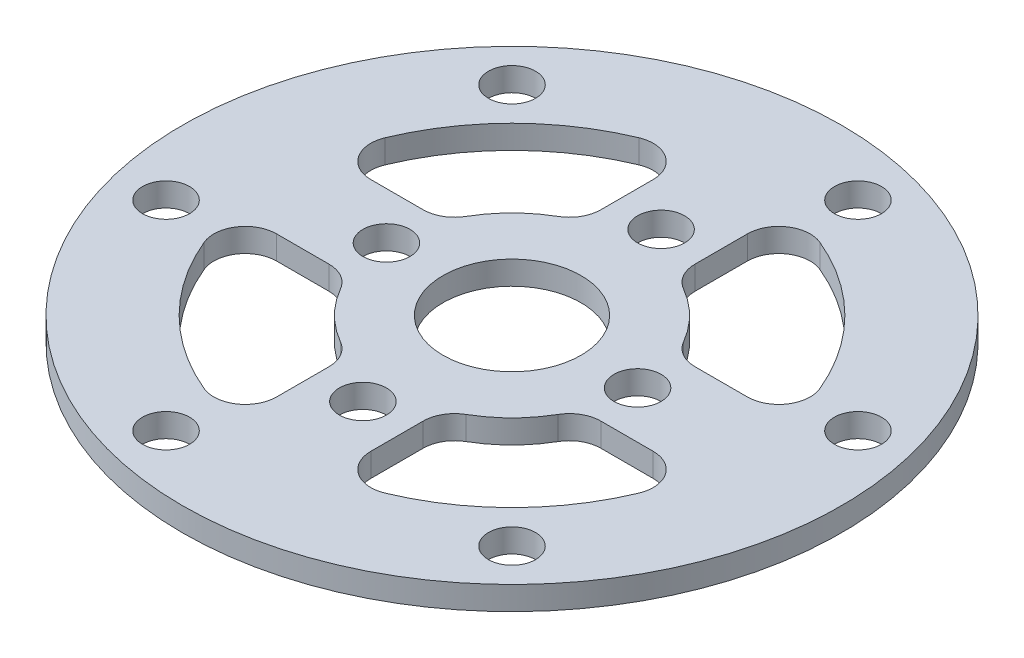
SolidWorks part; units mm, degrees
material "Thornel Mat VMA"
ref_plane "Front Plane" through (0, 0, 0) normal (0, 0, 1) x (1, 0, 0)
ref_plane "Top Plane" through (0, 0, 0) normal (0, 1, 0) x (1, 0, 0)
ref_plane "Right Plane" through (0, 0, 0) normal (1, 0, 0) x (0, 0, -1)
sketch "Sketch1" plane through (0, 0, 0) normal (0, 1, 0) x (1, 0, 0)
  line L0 (0, 0) -> (-21, 0) construction
  line L1 (0, 0) -> (0, 21) construction
  line L2 (0, 0) -> (21, 0) construction
  line L3 (0, 0) -> (0, -21) construction
  line L4 (-8.6603, 3) -> (-12, 3)
  line L5 (-8.6603, -3) -> (-12, -3)
  line L6 (-3, -8.6603) -> (-3, -12)
  line L7 (3, 8.6603) -> (3, 12)
  line L8 (8.6603, -3) -> (12, -3)
  line L9 (3, -8.6603) -> (3, -12)
  line L10 (-3, 8.6603) -> (-3, 12)
  line L11 (8.6603, 3) -> (12, 3)
  line L12 (-20.7846, -3) -> (-21, -3)
  line L13 (-3, -20.7846) -> (-3, -21)
  line L14 (0, -3) -> (-21, -3) construction
  line L15 (0, 3) -> (-21, 3) construction
  line L16 (-3, 0) -> (-3, -21) construction
  line L17 (-3, 0) -> (-3, 21) construction
  line L18 (0, 3) -> (21, 3) construction
  line L19 (3, 0) -> (3, 21) construction
  line L20 (3, 0) -> (3, -21) construction
  line L21 (0, -3) -> (21, -3) construction
  line L22 (-4.6587, -17.3867) -> (4.6587, 17.3867) construction
  line L23 (-17.3867, -4.6587) -> (17.3867, 4.6587) construction
  line L30 (12.7279, -12.7279) -> (-14.8492, 14.8492) construction
  circle A0 centre (0, 0) radius 4.4
  circle A1 centre (0, 0) radius 8 construction
  circle A2 centre (0, 0) radius 21
  arc A3 (-6.9282, -4) -> (-4, -6.9282) centre (0, 0) ccw
  arc A4 (-13.8462, -5.7692) -> (-5.7692, -13.8462) centre (0, 0) ccw
  arc A5 (5.7692, -13.8462) -> (13.8462, -5.7692) centre (0, 0) ccw
  arc A6 (4, -6.9282) -> (6.9282, -4) centre (0, 0) ccw
  arc A7 (6.9282, 4) -> (4, 6.9282) centre (0, 0) ccw
  arc A8 (13.8462, 5.7692) -> (5.7692, 13.8462) centre (0, 0) ccw
  arc A9 (-5.7692, -13.8462) -> (-3, -12) centre (-5, -12) ccw
  arc A10 (-3, -8.6603) -> (-4, -6.9282) centre (-5, -8.6603) ccw
  arc A11 (-6.9282, -4) -> (-8.6603, -3) centre (-8.6603, -5) ccw
  arc A12 (-12, -3) -> (-13.8462, -5.7692) centre (-12, -5) ccw
  arc A13 (-4, 6.9282) -> (-6.9282, 4) centre (0, 0) ccw
  arc A14 (-5.7692, 13.8462) -> (-13.8462, 5.7692) centre (0, 0) ccw
  arc A15 (-6.9282, 4) -> (-8.6603, 3) centre (-8.6603, 5) cw
  arc A16 (-13.8462, 5.7692) -> (-12, 3) centre (-12, 5) ccw
  arc A17 (-3, 8.6603) -> (-4, 6.9282) centre (-5, 8.6603) cw
  arc A18 (-3, 12) -> (-5.7692, 13.8462) centre (-5, 12) ccw
  arc A19 (8.6603, 3) -> (6.9282, 4) centre (8.6603, 5) cw
  arc A20 (12, 3) -> (13.8462, 5.7692) centre (12, 5) ccw
  arc A21 (5.7692, 13.8462) -> (3, 12) centre (5, 12) ccw
  arc A22 (3, 8.6603) -> (4, 6.9282) centre (5, 8.6603) ccw
  arc A23 (3, -8.6603) -> (4, -6.9282) centre (5, -8.6603) cw
  arc A24 (3, -12) -> (5.7692, -13.8462) centre (5, -12) ccw
  arc A25 (8.6603, -3) -> (6.9282, -4) centre (8.6603, -5) ccw
  arc A26 (12, -3) -> (13.8462, -5.7692) centre (12, -5) cw
  circle A27 centre (-8, 0) radius 1.5
  circle A28 centre (8, 0) radius 1.5
  circle A29 centre (0, 0) radius 9.5 construction
  circle A30 centre (0, 9.5) radius 1.5
  circle A31 centre (0, -9.5) radius 1.5
  circle A35 centre (0, 0) radius 18 construction
  circle A36 centre (-12.7279, 12.7279) radius 1.5
  circle A37 centre (4.6587, 17.3867) radius 1.5
  circle A38 centre (0, 0) radius 4.4
  circle A39 centre (17.3867, 4.6587) radius 1.5
  circle A40 centre (0, 0) radius 4.4
  circle A41 centre (12.7279, -12.7279) radius 1.5
  circle A42 centre (0, 0) radius 4.4
  circle A43 centre (-4.6587, -17.3867) radius 1.5
  circle A44 centre (0, 0) radius 4.4
  circle A45 centre (-17.3867, -4.6587) radius 1.5
  circle A46 centre (0, 0) radius 4.4
  point P102 (0, 0)
  point P122 (0, 0)
  dimension "D1" = 3
  dimension "D5" = 2
  dimension "D6" = 2
  dimension "D7" = 2
  dimension "D8" = 42
  dimension "D9" = 15
  dimension "D10" = 16
  dimension "D11" = 8
  dimension "D12" = 8.8
  dimension "D13" = 2
  dimension "D14" = 2
  dimension "D15" = 19
  dimension "D16" = 6
  dimension "D17" = 3
  dimension "D18" = 3
  dimension "D19" = 3
  dimension "D20" = 3
  dimension "D21" = 3
  dimension "D22" = 6
  dimension "D25" = 3
  dimension "D23" = 60
  dimension "D24" = 120
  dimension "D2" = 3
  dimension "D3" = 3
  dimension "D4" = 3
extrude "Boss-Extrude1" add sketch "Sketch1" along normal blind 1.5
